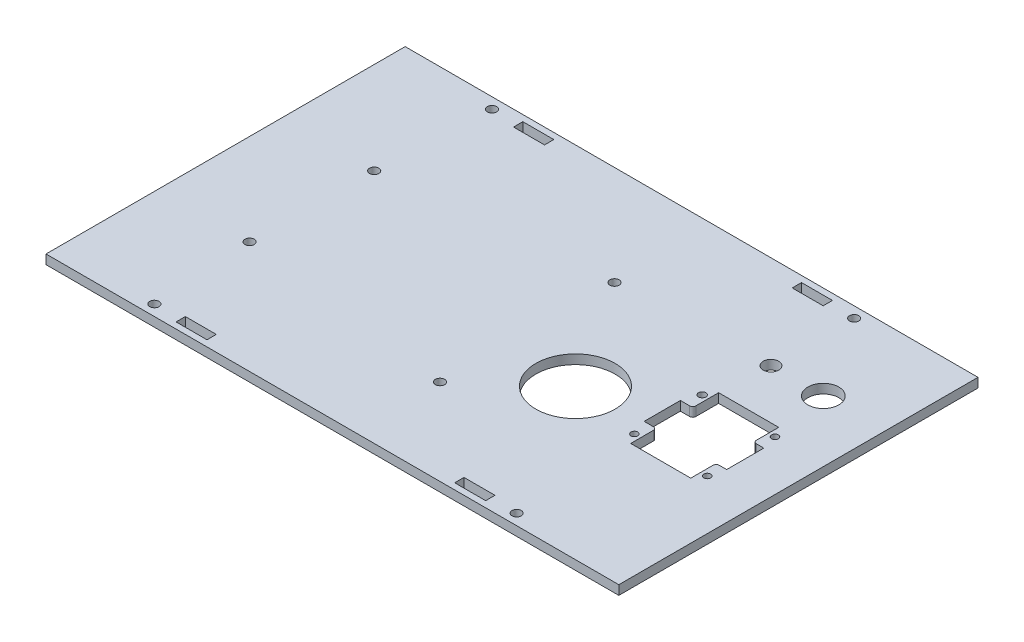
SolidWorks part; units mm, degrees
ref_plane "Front Plane" through (0, 0, 0) normal (0, 0, 1) x (1, 0, 0)
ref_plane "Top Plane" through (0, 0, 0) normal (0, 1, 0) x (1, 0, 0)
ref_plane "Right Plane" through (0, 0, 0) normal (1, 0, 0) x (0, 0, -1)
sketch "Sketch1" plane through (0, 0, 0) normal (0, 1, 0) x (1, 0, 0)
  line L1 (-92.5, -58) -> (92.5, -58)
  line L2 (-92.5, -58) -> (-92.5, 58)
  line L3 (-92.5, 58) -> (92.5, 58)
  line L4 (92.5, -58) -> (92.5, 58)
  line L5 (-92.5, -58) -> (92.5, 58) construction
  line L6 (-92.5, 58) -> (92.5, -58) construction
  point P0 (0, 0)
  dimension "D1" = 116
  dimension "D2" = 185
  dimension "D3" = 58
extrude "Boss-Extrude1" add sketch "Sketch1" along normal blind 3
sketch "Sketch8" plane through (0, 3, 0) normal (0, 1, 0) x (1, 0, 0)
  circle A0 centre (-62.7647, 18.2642) radius 1.5
  circle A1 centre (-63.0167, -21.735) radius 1.5
  circle A2 centre (7.2843, 25.8231) radius 1.5
  circle A3 centre (6.9315, -30.1758) radius 1.5
  dimension "D1" = 3
  dimension "D2" = 3
  dimension "D3" = 3
  dimension "D4" = 3
extrude "Cut-Extrude3" cut sketch "Sketch8" against normal blind 3
sketch "Sketch10" plane through (0, 3, 0) normal (0, 1, 0) x (1, 0, 0)
  line L0 (-92.5, -58) -> (92.5, -58) construction
  line L5 (92.5, -58) -> (92.5, 58) construction
  line L6 (50.9126, -8.2311) -> (53.9126, -8.2311)
  line L7 (50.9126, 11.3189) -> (50.9126, -16.0811) construction
  line L8 (54.9126, 10.9189) -> (54.9126, -15.6811) construction
  line L9 (54.9126, -9.2311) -> (54.9126, -16.5811)
  line L10 (51.4126, -16.5811) -> (77.8126, -16.5811) construction
  line L11 (54.9126, -16.5811) -> (74.3126, -16.5811)
  line L12 (74.3126, -16.5811) -> (74.3126, -9.3811)
  line L13 (75.325, -8.3811) -> (73.1126, -8.3811) construction
  line L14 (74.3126, -16.3811) -> (74.3126, 11.6189) construction
  line L15 (75.3126, -8.3811) -> (77.7126, -8.3811)
  line L16 (50.9126, -8.2311) -> (50.9126, 3.4689)
  line L17 (50.9126, 3.4689) -> (53.9141, 3.4733)
  line L18 (54.9126, 4.4733) -> (54.9126, 11.8189)
  line L19 (77.8126, 11.8189) -> (51.4126, 11.8189) construction
  line L20 (54.9126, 11.8189) -> (74.3126, 11.8189)
  line L21 (74.3126, 11.8189) -> (74.3126, 4.6189)
  line L22 (73.1126, 3.6189) -> (75.325, 3.6189) construction
  line L23 (75.3126, 3.6189) -> (77.7126, 3.6189)
  line L24 (77.7126, 3.6189) -> (77.7126, -8.3811)
  circle A0 centre (52.8626, 8.5689) radius 1.2
  circle A1 centre (52.8626, -13.3311) radius 1.1
  circle A2 centre (76.3626, -13.3311) radius 1.1
  circle A3 centre (76.3626, 8.5689) radius 1.1
  arc A4 (53.9141, 3.4733) -> (54.9126, 4.4733) centre (53.9126, 4.4733) ccw
  arc A5 (53.9126, -8.2311) -> (54.9126, -9.2311) centre (53.9126, -9.2311) cw
  arc A6 (74.3126, -9.3811) -> (75.3126, -8.3811) centre (75.3126, -9.3811) cw
  arc A7 (75.3126, 3.6189) -> (74.3126, 4.6189) centre (75.3126, 4.6189) cw
  circle A8 centre (55.8126, 27.817) radius 2.5
  circle A9 centre (72.7358, 27.817) radius 5
  circle A11 centre (30, -9.5) radius 12.8003
  point P42 (54.9126, 3.4748)
  point P45 (54.9126, -8.2311)
  point P48 (74.3126, -8.3811)
  point P51 (74.3126, 3.6189)
  point P58 (0, 0)
  dimension "D1" = 1
  dimension "D2" = 1
  dimension "D3" = 1
  dimension "D4" = 1
  dimension "D5" = 5
  dimension "D6" = 48.5
  dimension "D7" = 62.5
extrude "Cut-Extrude6" cut sketch "Sketch10" against normal blind 3
sketch "Sketch11" plane through (0, 3, 0) normal (0, 1, 0) x (1, 0, 0)
  line L0 (37.5, -56) -> (47.5, -56) construction
  line L1 (-52.5, 53) -> (-42.5, 53)
  line L2 (-52.5, 53) -> (-52.5, 56)
  line L3 (-52.5, 56) -> (-42.5, 56)
  line L4 (-42.5, 53) -> (-42.5, 56)
  line L5 (37.5, 53) -> (47.5, 53)
  line L6 (37.5, 53) -> (37.5, 56)
  line L7 (37.5, 56) -> (47.5, 56)
  line L8 (47.5, 53) -> (47.5, 56)
  line L9 (-52.5, -56) -> (-42.5, -56)
  line L10 (-52.5, -56) -> (-52.5, -53)
  line L11 (-52.5, -53) -> (-42.5, -53)
  line L12 (-42.5, -56) -> (-42.5, -53)
  line L13 (37.5, -56) -> (47.5, -56)
  line L14 (37.5, -56) -> (37.5, -53)
  line L15 (37.5, -53) -> (47.5, -53)
  line L16 (47.5, -56) -> (47.5, -53)
  line L17 (92.5, 58) -> (-92.5, 58) construction
  line L18 (-92.5, -58) -> (92.5, -58) construction
  dimension "D1" = 2
  dimension "D2" = 2
  dimension "D3" = 2
extrude "Cut-Extrude7" cut sketch "Sketch11" against normal blind 3
sketch "Sketch13" plane through (0, 0, 0) normal (0, -1, 0) x (1, 0, 0)
  line L0 (54.5, -53) -> (57.5, -56) construction
  line L1 (-62.5, -53) -> (-59.5, -56) construction
  line L2 (-59.5, 53) -> (-62.5, 56) construction
  line L3 (57.5, 53) -> (54.5, 56) construction
  line L4 (54.5, 53) -> (54.5, 56) construction
  line L5 (-77.5, 56) -> (77.5, 56) construction
  circle A0 centre (56, -54.5) radius 1.5
  circle A1 centre (-60.9358, -54.5069) radius 1.5069
  circle A2 centre (-61, 54.5) radius 1.5
  circle A3 centre (56, 54.5) radius 1.5
extrude "Cut-Extrude8" cut sketch "Sketch13" against normal blind 3
